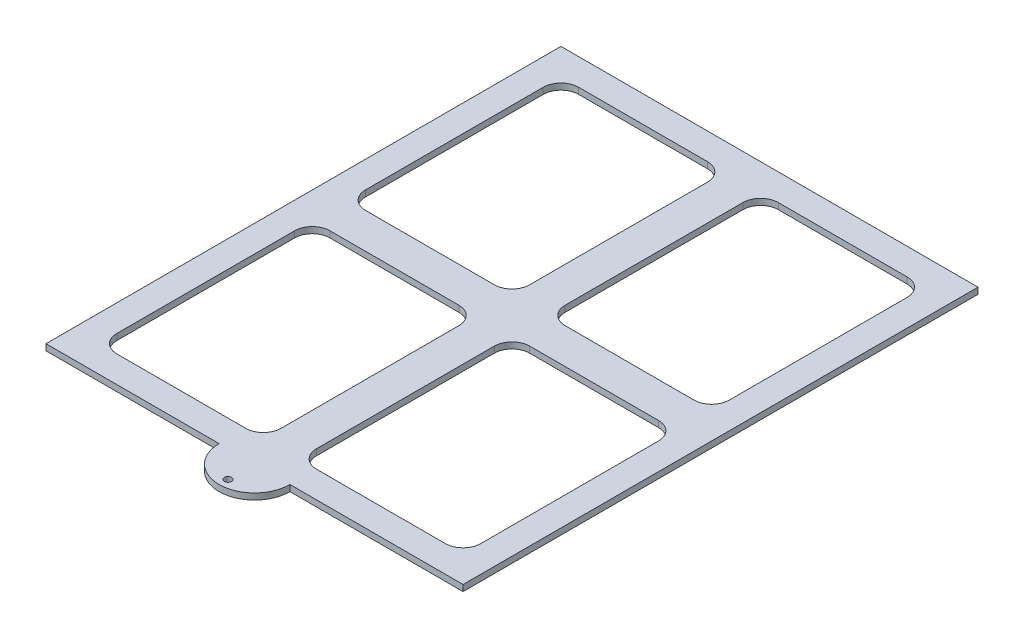
SolidWorks part; units mm, degrees
ref_plane "Front Plane" through (0, 0, 0) normal (0, 0, 1) x (1, 0, 0)
ref_plane "Top Plane" through (0, 0, 0) normal (0, 1, 0) x (1, 0, 0)
ref_plane "Right Plane" through (0, 0, 0) normal (1, 0, 0) x (0, 0, -1)
sketch "Sketch1" plane through (0, 0, 0) normal (0, 1, 0) x (1, 0, 0)
  line L1 (-117.8, -145.45) -> (117.8, -145.45)
  line L2 (-117.8, -145.45) -> (-117.8, 145.45)
  line L3 (-117.8, 145.45) -> (117.8, 145.45)
  line L4 (117.8, -145.45) -> (117.8, 145.45)
  line L5 (-117.8, -145.45) -> (117.8, 145.45) construction
  line L6 (-117.8, 145.45) -> (117.8, -145.45) construction
  point P0 (0, 0)
  dimension "D1" = 235.6
  dimension "D2" = 290.9
extrude "Boss-Extrude1" add sketch "Sketch1" along normal blind 3.5
sketch "Sketch2" plane through (0, 3.5, 0) normal (0, 1, 0) x (1, 0, 0)
  line L0 (117.8, 145.45) -> (-117.8, 145.45) construction
  line L1 (-107.8, -135.45) -> (107.8, -135.45)
  line L2 (-107.8, -135.45) -> (-107.8, 135.45)
  line L3 (-107.8, 135.45) -> (107.8, 135.45)
  line L4 (107.8, -135.45) -> (107.8, 135.45)
  line L5 (-107.8, -135.45) -> (107.8, 135.45) construction
  line L6 (-107.8, 135.45) -> (107.8, -135.45) construction
  line L7 (117.8, -145.45) -> (117.8, 145.45) construction
  point P0 (0, 0)
  dimension "D1" = 10
  dimension "D2" = 10
sketch "Sketch3" plane through (0, 3.5, 0) normal (0, 1, 0) x (1, 0, 0)
  line L0 (-117.8, -145.45) -> (117.8, -145.45) construction
  line L1 (-20, -145.45) -> (20, -145.45)
  arc A0 (-20, -145.45) -> (20, -145.45) centre (0, -145.45) ccw
  dimension "D1" = 20
extrude "Boss-Extrude2" add sketch "Sketch3" against normal blind 3.5
sketch "Sketch4" plane through (0, 3.5, 0) normal (0, 1, 0) x (1, 0, 0)
  line L0 (-117.8, -145.45) -> (-20, -145.45) construction
  circle A0 centre (0, -160.45) radius 2
  dimension "D1" = 4
  dimension "D2" = 15
extrude "Cut-Extrude1" cut sketch "Sketch4" against normal blind 3.5
sketch "Sketch5" plane through (0, 3.5, 0) normal (0, 1, 0) x (1, 0, 0)
  line L0 (-117.8, 145.45) -> (-117.8, -145.45) construction
  line L1 (-102.8, 130.45) -> (-10, 130.45)
  line L2 (-102.8, 130.45) -> (-102.8, 10)
  line L3 (-102.8, 10) -> (-10, 10)
  line L4 (-10, 130.45) -> (-10, 10)
  line L5 (10, 130.45) -> (102.8, 130.45)
  line L6 (10, 130.45) -> (10, 10)
  line L7 (10, 10) -> (102.8, 10)
  line L8 (102.8, 130.45) -> (102.8, 10)
  line L9 (-102.8, -130.45) -> (-10, -130.45)
  line L10 (-102.8, -130.45) -> (-102.8, -10)
  line L11 (-102.8, -10) -> (-10, -10)
  line L12 (-10, -130.45) -> (-10, -10)
  line L13 (10, -10) -> (102.8, -10)
  line L14 (10, -10) -> (10, -130.45)
  line L15 (10, -130.45) -> (102.8, -130.45)
  line L16 (102.8, -10) -> (102.8, -130.45)
  line L17 (117.8, -145.45) -> (117.8, 145.45) construction
  line L18 (117.8, 145.45) -> (-117.8, 145.45) construction
  line L19 (20, -145.45) -> (117.8, -145.45) construction
  line L20 (-117.8, -145.45) -> (-20, -145.45) construction
  line L21 (0, 145.45) -> (0, -165.45) construction
  line L22 (-117.8, 0) -> (117.8, 0) construction
  arc A0 (-20, -145.45) -> (20, -145.45) centre (0, -145.45) ccw construction
  dimension "D1" = 20
  dimension "D2" = 20
  dimension "D3" = 20
  dimension "D4" = 20
  dimension "D5" = 15
  dimension "D6" = 15
  dimension "D7" = 15
  dimension "D8" = 15
  dimension "D9" = 15
  dimension "D10" = 15
  dimension "D11" = 15
  dimension "D12" = 15
  dimension "D13" = 10
  dimension "D14" = 10
  dimension "D15" = 10
  dimension "D16" = 10
extrude "Cut-Extrude2" cut sketch "Sketch5" against normal blind 10
fillet "Fillet1" radius 10 16 edges at (102.8, 1.75, -130.45) (102.8, 1.75, 10) (102.8, 1.75, 130.45) (10, 1.75, 130.45) (-10, 1.75, 10) (-10, 1.75, 130.45) (-102.8, 1.75, 130.45) (-102.8, 1.75, 10) (-10, 1.75, -10) (-102.8, 1.75, -10) (-102.8, 1.75, -130.45) (-10, 1.75, -130.45) (10, 1.75, 10) (10, 1.75, -130.45) (10, 1.75, -10) (102.8, 1.75, -10)
